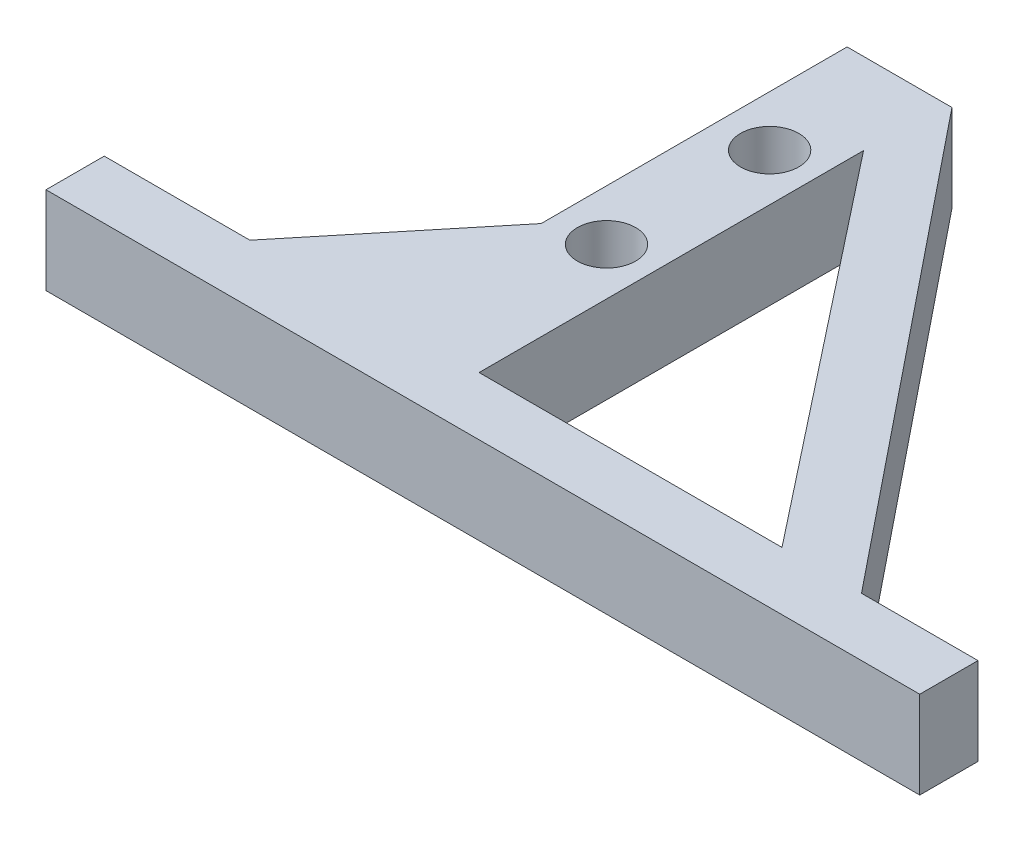
SolidWorks part; units mm, degrees
ref_plane "Front Plane" through (0, 0, 0) normal (0, 0, 1) x (1, 0, 0)
ref_plane "Top Plane" through (0, 0, 0) normal (0, 1, 0) x (1, 0, 0)
ref_plane "Right Plane" through (0, 0, 0) normal (1, 0, 0) x (0, 0, -1)
sketch "Sketch1" plane through (0, 0, 0) normal (0, 1, 0) x (1, 0, 0)
  line L0 (0, 0) -> (190.5, 0)
  line L1 (190.5, 0) -> (190.5, 12.7)
  line L2 (0, 0) -> (0, 12.7)
  line L3 (0, 12.7) -> (31.75, 12.7)
  line L7 (83.2225, 114.3) -> (165.1, 12.7)
  line L8 (165.1, 12.7) -> (190.5, 12.7)
  line L14 (81.7258, 96.52) -> (81.7258, 12.7)
  line L15 (81.7258, 12.7) -> (147.7658, 12.7)
  line L16 (81.7258, 96.52) -> (147.7658, 12.7)
  line L17 (83.2225, 114.3) -> (60.3625, 114.3)
  line L18 (60.3625, 114.3) -> (60.3625, 47.5946)
  line L19 (31.75, 12.7) -> (60.3625, 47.5946)
  circle A0 centre (71.4132, 86.36) radius 6.35
  circle A1 centre (71.4132, 50.8) radius 6.35
  dimension "D5" = 12.7
  dimension "D6" = 12.7
  dimension "D1" = 190.5
  dimension "D2" = 12.7
  dimension "D3" = 12.7
  dimension "D4" = 31.75
  dimension "D7" = 22.86
  dimension "D8" = 35.56
  dimension "D9" = 83.82
  dimension "D10" = 66.04
  dimension "D11" = 25.4
  dimension "D12" = 50.8
extrude "Boss-Extrude1" add sketch "Sketch1" along normal blind 19.05
